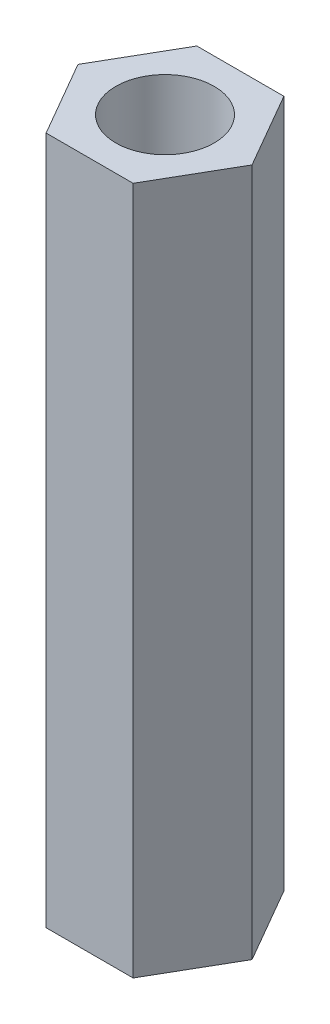
SolidWorks part; units mm, degrees
ref_plane "Front" through (0, 0, 0) normal (0, 0, 1) x (1, 0, 0)
ref_plane "Top" through (0, 0, 0) normal (0, 1, 0) x (1, 0, 0)
ref_plane "Right" through (0, 0, 0) normal (1, 0, 0) x (0, 0, -1)
sketch "草图1" plane through (0, 0, 0) normal (0, 1, 0) x (1, 0, 0)
  line L1 (-1.3279, 2.3) -> (-2.6558, 0)
  line L2 (-2.6558, 0) -> (-1.3279, -2.3)
  line L3 (-1.3279, -2.3) -> (1.3279, -2.3)
  line L4 (1.3279, -2.3) -> (2.6558, 0)
  line L5 (2.6558, 0) -> (1.3279, 2.3)
  line L6 (1.3279, 2.3) -> (-1.3279, 2.3)
  circle A0 centre (0, 0) radius 2.3 construction
  circle A1 centre (0, 0) radius 1.5 construction
  dimension "D2" = 3
  dimension "D1" = 4.6
extrude "凸台-拉伸1" add sketch "草图1" along normal blind 21
sketch "草图3" plane through (0, 21, 0) normal (0, 1, 0) x (1, 0, 0)
  circle A0 centre (0, 0) radius 1.5
  dimension "D1" = 3
sketch "草图4" plane through (0, 0, 0) normal (0, -1, 0) x (1, 0, 0)
  circle A0 centre (0, 0) radius 1.5
  dimension "D1" = 3
extrude "切除-拉伸1" cut sketch "草图4" against normal up to surface (21 mm away) up to face at (0, 21, 0)
cosmetic thread "装饰螺纹线1" parameters "D2"=4
ref_plane "基准面1" through (0, 10.5, 0) normal (0, 1, 0) x (1, 0, 0)
